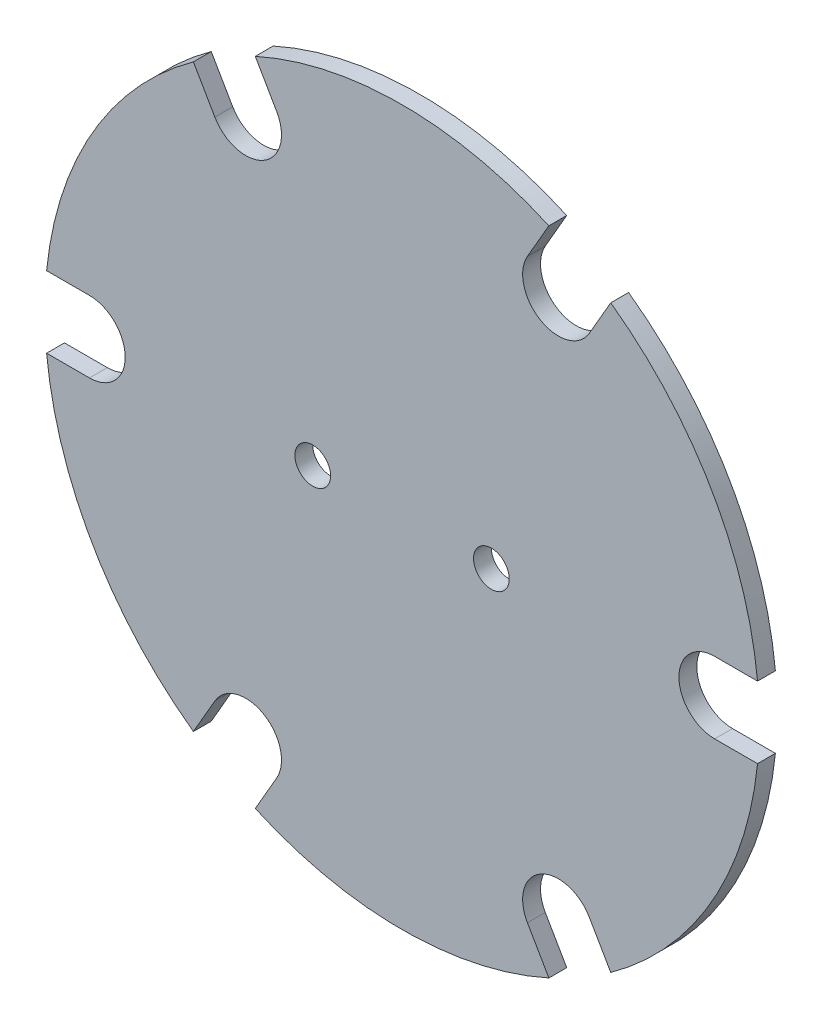
SolidWorks part; units mm, degrees
ref_plane "前视基准面" through (0, 0, 0) normal (0, 0, 1) x (1, 0, 0)
ref_plane "上视基准面" through (0, 0, 0) normal (0, 1, 0) x (1, 0, 0)
ref_plane "右视基准面" through (0, 0, 0) normal (1, 0, 0) x (0, 0, -1)
sketch "草图1" plane through (0, 0, 0) normal (0, 0, 1) x (1, 0, 0)
  line L0 (-35, 4) -> (-39.7995, 4)
  line L1 (-35, -4) -> (-39.7995, -4)
  line L2 (-14.0359, 32.3109) -> (-16.4356, 36.4674)
  line L3 (-20.9641, 28.3109) -> (-23.3639, 32.4674)
  line L4 (20.9641, 28.3109) -> (23.3639, 32.4674)
  line L5 (14.0359, 32.3109) -> (16.4356, 36.4674)
  line L6 (35, -4) -> (39.7995, -4)
  line L7 (35, 4) -> (39.7995, 4)
  line L8 (14.0359, -32.3109) -> (16.4356, -36.4674)
  line L9 (20.9641, -28.3109) -> (23.3639, -32.4674)
  line L10 (-20.9641, -28.3109) -> (-23.3639, -32.4674)
  line L11 (-14.0359, -32.3109) -> (-16.4356, -36.4674)
  arc A0 (-39.7995, -4) -> (-23.3639, -32.4674) centre (0, 0) ccw
  arc A1 (-35, -4) -> (-35, 4) centre (-35, 0) ccw
  arc A2 (-20.9641, 28.3109) -> (-14.0359, 32.3109) centre (-17.5, 30.3109) ccw
  arc A3 (14.0359, 32.3109) -> (20.9641, 28.3109) centre (17.5, 30.3109) ccw
  arc A4 (35, 4) -> (35, -4) centre (35, 0) ccw
  arc A5 (20.9641, -28.3109) -> (14.0359, -32.3109) centre (17.5, -30.3109) ccw
  arc A6 (-14.0359, -32.3109) -> (-20.9641, -28.3109) centre (-17.5, -30.3109) ccw
  arc A7 (-23.3639, 32.4674) -> (-39.7995, 4) centre (0, 0) ccw
  arc A8 (16.4356, 36.4674) -> (-16.4356, 36.4674) centre (0, 0) ccw
  arc A9 (39.7995, 4) -> (23.3639, 32.4674) centre (0, 0) ccw
  arc A10 (-16.4356, -36.4674) -> (16.4356, -36.4674) centre (0, 0) ccw
  arc A11 (23.3639, -32.4674) -> (39.7995, -4) centre (0, 0) ccw
  circle A12 centre (0, 0) radius 2.5 construction
  circle A13 centre (-10, 0) radius 2
  circle A14 centre (10, 0) radius 2
  point P35 (0, 0)
  point P38 (0, 0)
  dimension "D1" = 80
  dimension "D2" = 35
  dimension "D4" = 4
  dimension "D5" = 5
  dimension "D6" = 4
  dimension "D8" = 4
  dimension "D3" = 6
  dimension "D7" = 10
  dimension "D9" = 10
extrude "凸台-拉伸1" add sketch "草图1" along normal blind 2
